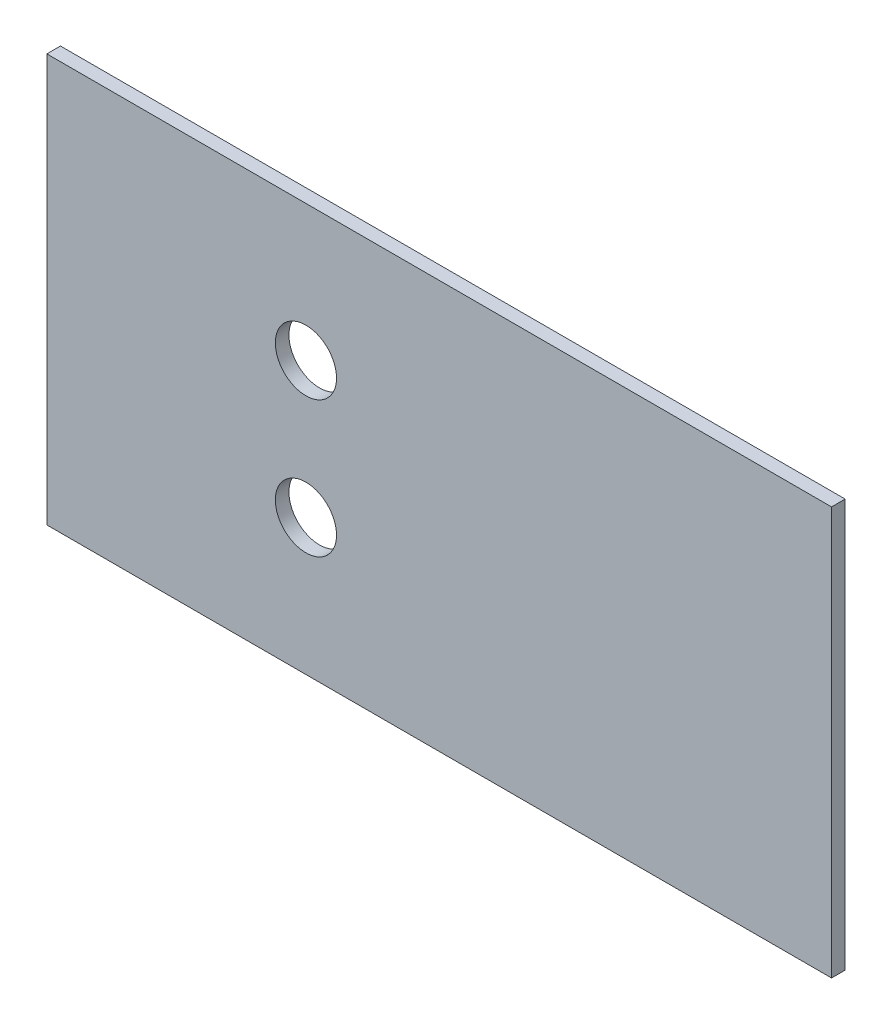
SolidWorks part; units mm, degrees
ref_plane "Front Plane" through (0, 0, 0) normal (0, 0, 1) x (1, 0, 0)
ref_plane "Top Plane" through (0, 0, 0) normal (0, 1, 0) x (1, 0, 0)
ref_plane "Right Plane" through (0, 0, 0) normal (1, 0, 0) x (0, 0, -1)
sketch "Sketch1" plane through (0, 0, 0) normal (0, 0, 1) x (1, 0, 0)
  line L0 (-49.6, 37) -> (8.1, 37)
  line L1 (8.1, 7) -> (-49.6, 7)
  line L14 (-49.6, 37) -> (-49.6, 7)
  line L15 (8.1, 37) -> (8.1, 7)
  circle A18 centre (-30.55, 17) radius 2.25
  circle A19 centre (-30.55, 27) radius 2.25
  point P24 (-49.6, 7)
  point P26 (8.1, 7)
  point P27 (-49.6, 37)
  point P28 (8.1, 37)
  dimension "D8" = 10
  dimension "D9" = 10
  dimension "D10" = 19.05
  dimension "D11" = 7
  dimension "D25" = 4.5
  dimension "D26" = 4.5
  dimension "D3" = 0
  dimension "D4" = 57.7
  dimension "D5" = 0
  dimension "D6" = 0
  dimension "D7" = 57.7
  dimension "D12" = 8.1
  dimension "D13" = 19.05
  dimension "D27" = 10
extrude "Boss-Extrude1" add sketch "Sketch1" along normal blind 1
